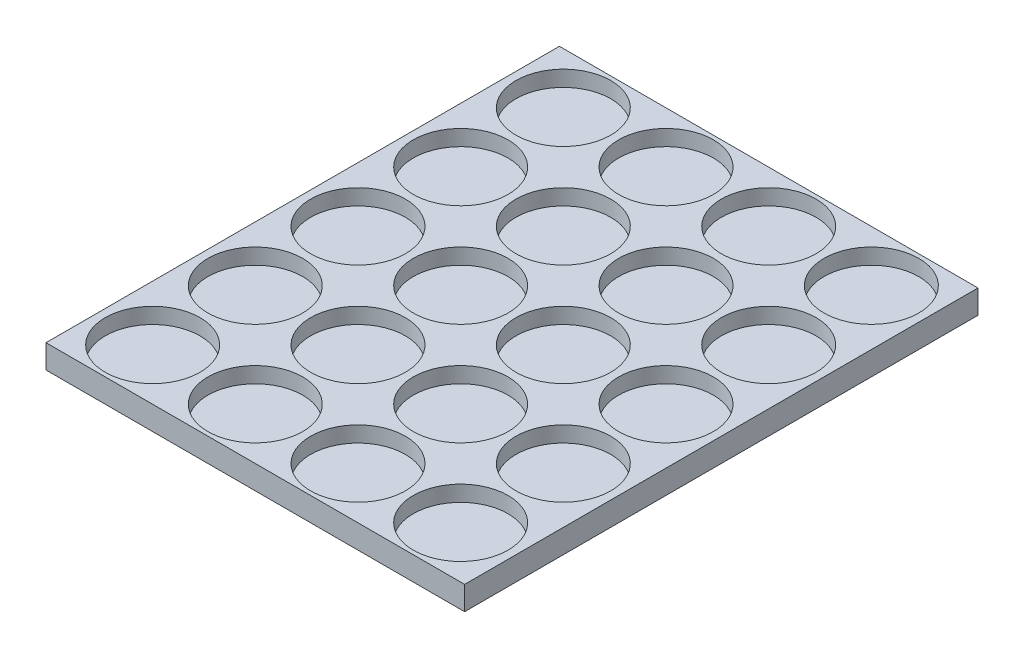
SolidWorks part; units mm, degrees
ref_plane "Front Plane" through (0, 0, 0) normal (0, 0, 1) x (1, 0, 0)
ref_plane "Top Plane" through (0, 0, 0) normal (0, 1, 0) x (1, 0, 0)
ref_plane "Right Plane" through (0, 0, 0) normal (1, 0, 0) x (0, 0, -1)
other "Configuration Table"
sketch "Sketch1" plane through (0, 0, 0) normal (0, 1, 0) x (1, 0, 0)
  line L1 (44, 25) -> (574, 25)
  line L2 (44, 25) -> (44, 675)
  line L3 (44, 675) -> (574, 675)
  line L4 (574, 25) -> (574, 675)
extrude "TPS_silikon_GN21_20_cukur_1" add sketch "Sketch1" along normal blind 30 from offset 9 separate body
sketch "Sketch2" plane through (0, 0, 0) normal (0, 1, 0) x (1, 0, 0)
  circle A0 centre (114, 610) radius 60
extrude "TPS_silikon_GN21_20_cukur_2" cut sketch "Sketch2" along normal blind 21 from offset 19
sketch "Sketch3" plane through (0, 0, 0) normal (0, 1, 0) x (1, 0, 0)
  circle A0 centre (114, 480) radius 60
extrude "TPS_silikon_GN21_20_cukur_3" cut sketch "Sketch3" along normal blind 21 from offset 19
sketch "Sketch4" plane through (0, 0, 0) normal (0, 1, 0) x (1, 0, 0)
  circle A0 centre (114, 350) radius 60
extrude "TPS_silikon_GN21_20_cukur_4" cut sketch "Sketch4" along normal blind 21 from offset 19
sketch "Sketch5" plane through (0, 0, 0) normal (0, 1, 0) x (1, 0, 0)
  circle A0 centre (114, 220) radius 60
extrude "TPS_silikon_GN21_20_cukur_5" cut sketch "Sketch5" along normal blind 21 from offset 19
sketch "Sketch6" plane through (0, 0, 0) normal (0, 1, 0) x (1, 0, 0)
  circle A0 centre (114, 90) radius 60
extrude "TPS_silikon_GN21_20_cukur_6" cut sketch "Sketch6" along normal blind 21 from offset 19
sketch "Sketch7" plane through (0, 0, 0) normal (0, 1, 0) x (1, 0, 0)
  circle A0 centre (244, 610) radius 60
extrude "TPS_silikon_GN21_20_cukur_7" cut sketch "Sketch7" along normal blind 21 from offset 19
sketch "Sketch8" plane through (0, 0, 0) normal (0, 1, 0) x (1, 0, 0)
  circle A0 centre (244, 480) radius 60
extrude "TPS_silikon_GN21_20_cukur_8" cut sketch "Sketch8" along normal blind 21 from offset 19
sketch "Sketch9" plane through (0, 0, 0) normal (0, 1, 0) x (1, 0, 0)
  circle A0 centre (244, 350) radius 60
extrude "TPS_silikon_GN21_20_cukur_9" cut sketch "Sketch9" along normal blind 21 from offset 19
sketch "Sketch10" plane through (0, 0, 0) normal (0, 1, 0) x (1, 0, 0)
  circle A0 centre (244, 220) radius 60
extrude "TPS_silikon_GN21_20_cukur_10" cut sketch "Sketch10" along normal blind 21 from offset 19
sketch "Sketch11" plane through (0, 0, 0) normal (0, 1, 0) x (1, 0, 0)
  circle A0 centre (244, 90) radius 60
extrude "TPS_silikon_GN21_20_cukur_11" cut sketch "Sketch11" along normal blind 21 from offset 19
sketch "Sketch12" plane through (0, 0, 0) normal (0, 1, 0) x (1, 0, 0)
  circle A0 centre (374, 610) radius 60
extrude "TPS_silikon_GN21_20_cukur_12" cut sketch "Sketch12" along normal blind 21 from offset 19
sketch "Sketch13" plane through (0, 0, 0) normal (0, 1, 0) x (1, 0, 0)
  circle A0 centre (374, 480) radius 60
extrude "TPS_silikon_GN21_20_cukur_13" cut sketch "Sketch13" along normal blind 21 from offset 19
sketch "Sketch14" plane through (0, 0, 0) normal (0, 1, 0) x (1, 0, 0)
  circle A0 centre (374, 350) radius 60
extrude "TPS_silikon_GN21_20_cukur_14" cut sketch "Sketch14" along normal blind 21 from offset 19
sketch "Sketch15" plane through (0, 0, 0) normal (0, 1, 0) x (1, 0, 0)
  circle A0 centre (374, 220) radius 60
extrude "TPS_silikon_GN21_20_cukur_15" cut sketch "Sketch15" along normal blind 21 from offset 19
sketch "Sketch16" plane through (0, 0, 0) normal (0, 1, 0) x (1, 0, 0)
  circle A0 centre (374, 90) radius 60
extrude "TPS_silikon_GN21_20_cukur_16" cut sketch "Sketch16" along normal blind 21 from offset 19
sketch "Sketch17" plane through (0, 0, 0) normal (0, 1, 0) x (1, 0, 0)
  circle A0 centre (504, 610) radius 60
extrude "TPS_silikon_GN21_20_cukur_17" cut sketch "Sketch17" along normal blind 21 from offset 19
sketch "Sketch18" plane through (0, 0, 0) normal (0, 1, 0) x (1, 0, 0)
  circle A0 centre (504, 480) radius 60
extrude "TPS_silikon_GN21_20_cukur_18" cut sketch "Sketch18" along normal blind 21 from offset 19
sketch "Sketch19" plane through (0, 0, 0) normal (0, 1, 0) x (1, 0, 0)
  circle A0 centre (504, 350) radius 60
extrude "TPS_silikon_GN21_20_cukur_19" cut sketch "Sketch19" along normal blind 21 from offset 19
sketch "Sketch20" plane through (0, 0, 0) normal (0, 1, 0) x (1, 0, 0)
  circle A0 centre (504, 220) radius 60
extrude "TPS_silikon_GN21_20_cukur_20" cut sketch "Sketch20" along normal blind 21 from offset 19
sketch "Sketch21" plane through (0, 0, 0) normal (0, 1, 0) x (1, 0, 0)
  circle A0 centre (504, 90) radius 60
extrude "TPS_silikon_GN21_20_cukur_21" cut sketch "Sketch21" along normal blind 21 from offset 19
